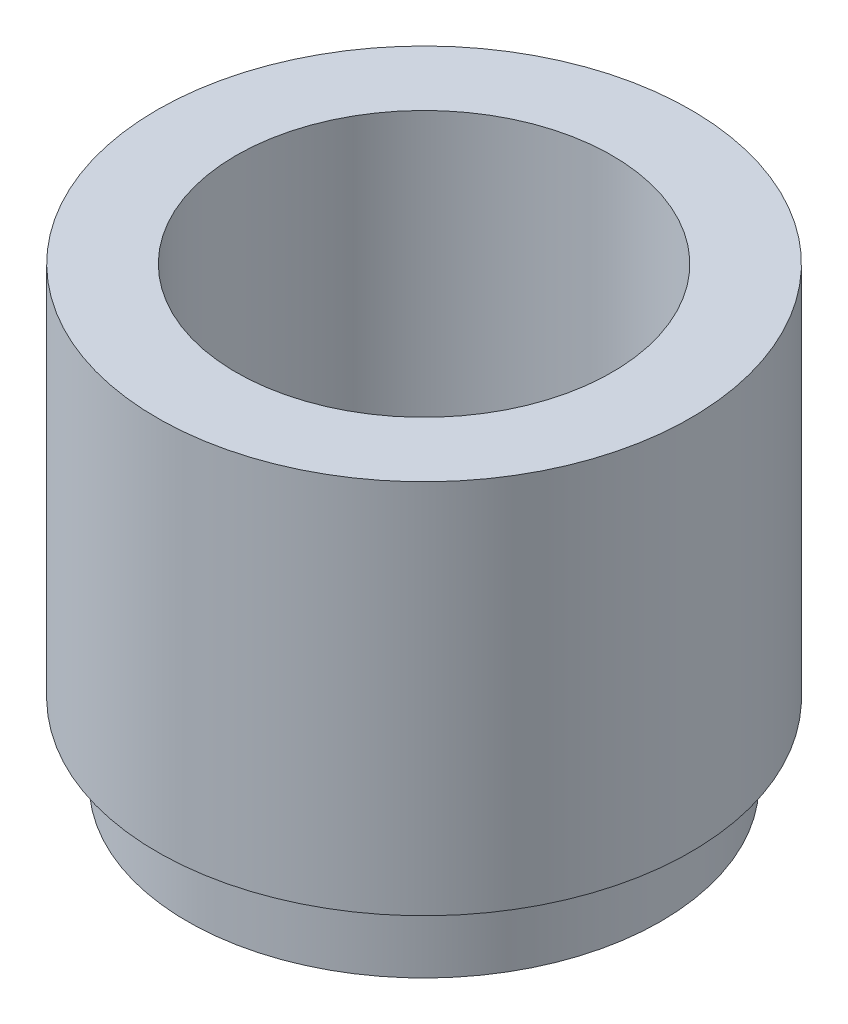
SolidWorks part; units mm, degrees
material "Brass"
ref_plane "Płaszczyzna przednia" through (0, 0, 0) normal (0, 0, 1) x (1, 0, 0)
ref_plane "Płaszczyzna górna" through (0, 0, 0) normal (0, 1, 0) x (1, 0, 0)
ref_plane "Płaszczyzna prawa" through (0, 0, 0) normal (1, 0, 0) x (0, 0, -1)
sketch "Sketch1" plane through (0, 0, 0) normal (0, 0, 1) x (1, 0, 0)
  line L0 (2.5, 0) -> (3.15, 0)
  line L1 (3.15, 0) -> (3.15, 1)
  line L2 (3.15, 1) -> (3.55, 1)
  line L3 (3.55, 1) -> (3.55, 6)
  line L4 (3.55, 6) -> (2.5, 6)
  line L5 (0, 6) -> (0, 0) construction
  line L6 (2.5, 0) -> (2.5, 6)
  dimension "D1" = 3.15
  dimension "D2" = 3.55
  dimension "D3" = 6
  dimension "D4" = 1
  dimension "D5" = 2.5
revolve "Revolve1" add sketch "Sketch1" angle 360 about L5
